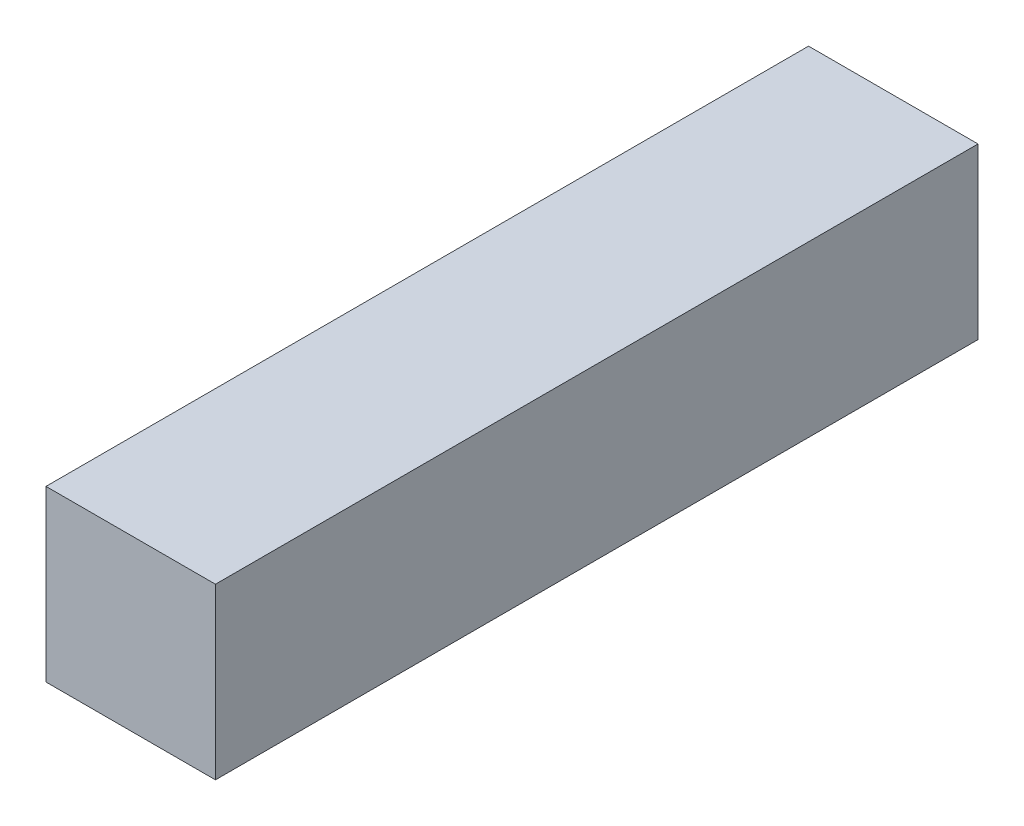
SolidWorks part; units mm, degrees
ref_plane "Front Plane" through (0, 0, 0) normal (0, 0, 1) x (1, 0, 0)
ref_plane "Top Plane" through (0, 0, 0) normal (0, 1, 0) x (1, 0, 0)
ref_plane "Right Plane" through (0, 0, 0) normal (1, 0, 0) x (0, 0, -1)
sketch "Sketch1" plane through (0, 0, 0) normal (0, 0, 1) x (1, 0, 0)
  line L1 (0, 0) -> (25.4, 0)
  line L2 (0, 0) -> (0, 25.4)
  line L3 (0, 25.4) -> (25.4, 25.4)
  line L4 (25.4, 0) -> (25.4, 25.4)
  dimension "D1" = 25.4
  dimension "D2" = 25.4
extrude "Boss-Extrude1" add sketch "Sketch1" along normal blind 114.3
